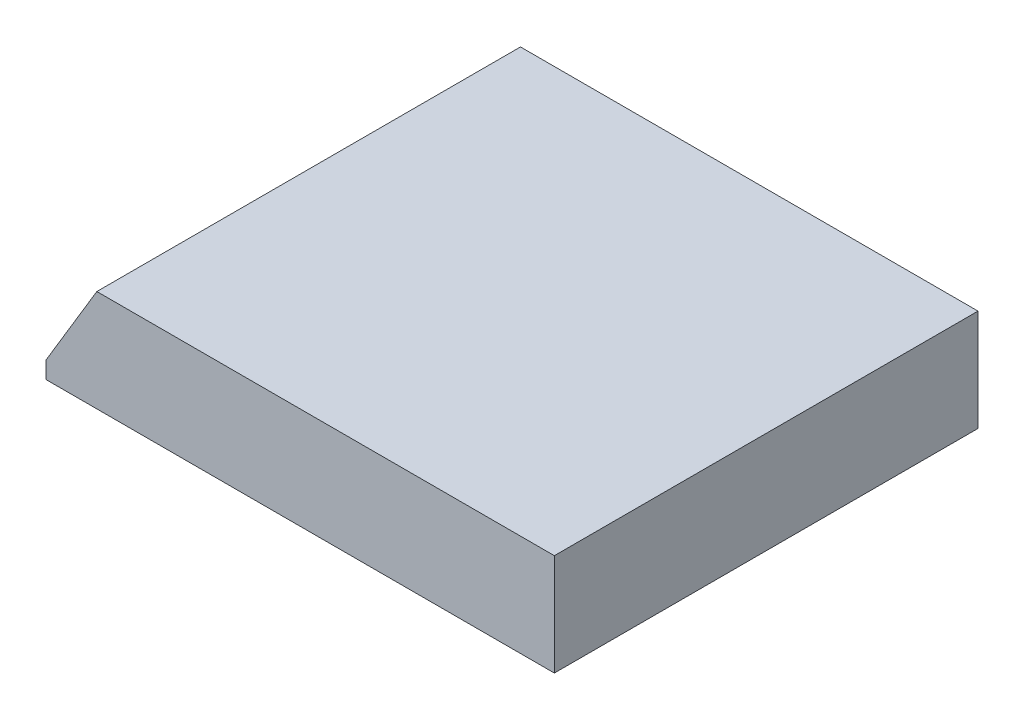
SolidWorks part; units mm, degrees
ref_plane "Front Plane" through (0, 0, 0) normal (0, 0, 1) x (1, 0, 0)
ref_plane "Top Plane" through (0, 0, 0) normal (0, 1, 0) x (1, 0, 0)
ref_plane "Right Plane" through (0, 0, 0) normal (1, 0, 0) x (0, 0, -1)
sketch "Sketch1" plane through (0, 0, 0) normal (0, 0, 1) x (1, 0, 0)
  line L1 (0, 0) -> (60, 0)
  line L2 (0, 0) -> (0, 12)
  line L3 (0, 12) -> (60, 12)
  line L4 (60, 0) -> (60, 12)
  line L5 (0, 0) -> (60, 12) construction
  line L6 (0, 12) -> (60, 0) construction
  point P4 (30, 6)
  dimension "D1" = 60
  dimension "D2" = 12
extrude "Boss-Extrude1" add sketch "Sketch1" along normal blind 50
sketch "Sketch2" plane through (0, 0, 50) normal (0, 0, 1) x (1, 0, 0)
  line L0 (0, 2) -> (6, 12)
  line L1 (0, 12) -> (0, 0) construction
  line L2 (60, 12) -> (0, 12) construction
  line L3 (6, 12) -> (0, 12)
  line L4 (0, 12) -> (0, 2)
  dimension "D1" = 6
  dimension "D2" = 10
extrude "Cut-Extrude1" cut sketch "Sketch2" against normal through all
